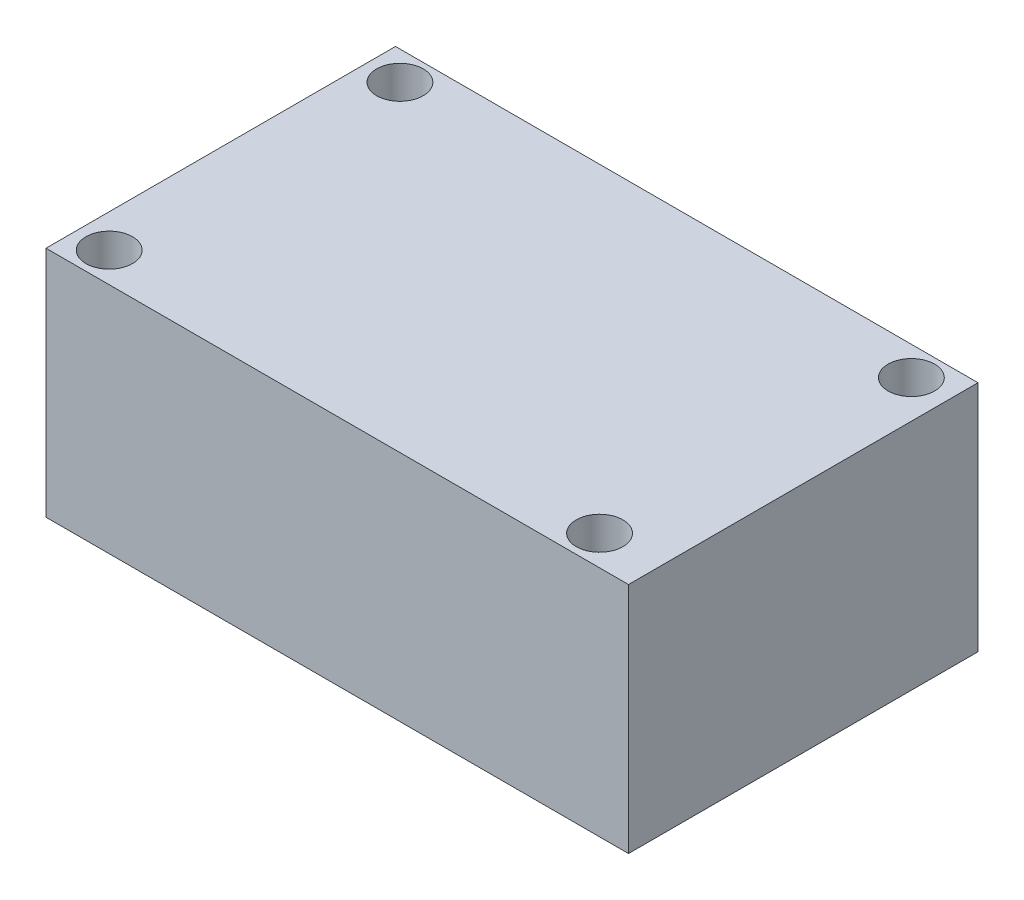
SolidWorks part; units mm, degrees
ref_plane "前视基准面" through (0, 0, 0) normal (0, 0, 1) x (1, 0, 0)
ref_plane "上视基准面" through (0, 0, 0) normal (0, 1, 0) x (1, 0, 0)
ref_plane "右视基准面" through (0, 0, 0) normal (1, 0, 0) x (0, 0, -1)
sketch "草图1" plane through (0, 0, 0) normal (0, 1, 0) x (1, 0, 0)
  line L1 (-14.582, 5.7832) -> (10.418, 5.7832)
  line L2 (-14.582, 5.7832) -> (-14.582, -9.2168)
  line L3 (-14.582, -9.2168) -> (10.418, -9.2168)
  line L4 (10.418, 5.7832) -> (10.418, -9.2168)
  line L5 (-14.582, 5.7832) -> (10.418, -9.2168) construction
  line L6 (-14.582, -9.2168) -> (10.418, 5.7832) construction
  point P4 (-2.082, -1.7168)
  dimension "D1" = 25
  dimension "D2" = 15
extrude "凸台-拉伸1" add sketch "草图1" along normal blind 10
sketch "草图2" plane through (0, 10, 0) normal (0, 1, 0) x (1, 0, 0)
  circle A0 centre (-13.1539, 4.5455) radius 1
  circle A1 centre (-13.1539, -7.9323) radius 1
  circle A2 centre (8.7955, 4.5455) radius 1
  circle A3 centre (7.8912, -7.9323) radius 1
  dimension "D1" = 2
extrude "切除-拉伸1" cut sketch "草图2" against normal through all
